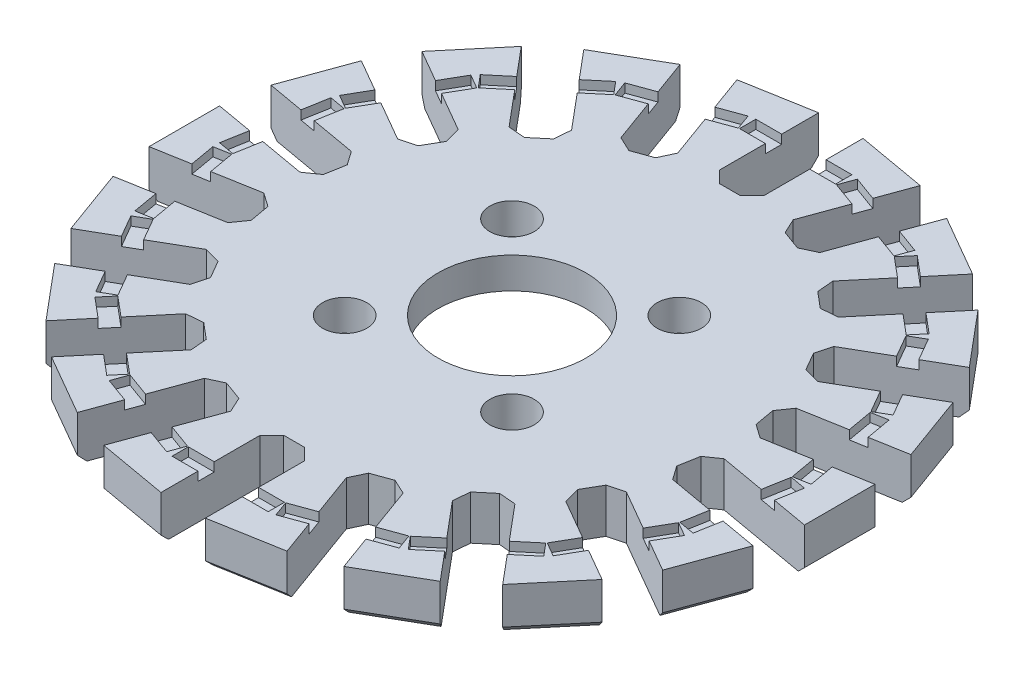
SolidWorks part; units mm, degrees
ref_plane "Front Plane" through (0, 0, 0) normal (0, 0, 1) x (1, 0, 0)
ref_plane "Top Plane" through (0, 0, 0) normal (0, 1, 0) x (1, 0, 0)
ref_plane "Right Plane" through (0, 0, 0) normal (1, 0, 0) x (0, 0, -1)
sketch "Sketch1" plane through (0, 0, 0) normal (0, 1, 0) x (1, 0, 0)
  line L0 (-1.5, 22.2355) -> (-1.5, 14.7355)
  line L1 (-1.5, 22.2355) -> (-6.1955, 21.4076)
  line L2 (-9.0145, 20.3815) -> (-13.1436, 17.9976)
  line L3 (-15.4418, 16.0692) -> (-18.5065, 12.4168)
  line L4 (-20.0065, 9.8187) -> (-21.6372, 5.3384)
  line L5 (-22.1582, 2.3839) -> (-22.1582, -2.3839)
  line L6 (-21.6372, -5.3384) -> (-20.0065, -9.8187)
  line L7 (-18.5065, -12.4168) -> (-15.4418, -16.0692)
  line L8 (-13.1436, -17.9976) -> (-9.0145, -20.3815)
  line L9 (-6.1955, -21.4076) -> (-1.5, -22.2355)
  line L10 (1.5, -22.2355) -> (6.1955, -21.4076)
  line L11 (9.0145, -20.3815) -> (13.1436, -17.9976)
  line L12 (15.4418, -16.0692) -> (18.5065, -12.4168)
  line L13 (20.0065, -9.8187) -> (21.6372, -5.3384)
  line L14 (22.1582, -2.3839) -> (22.1582, 2.3839)
  line L15 (21.6372, 5.3384) -> (20.0065, 9.8187)
  line L16 (18.5065, 12.4168) -> (15.4418, 16.0692)
  line L17 (13.1436, 17.9976) -> (9.0145, 20.3815)
  line L18 (6.1955, 21.4076) -> (1.5, 22.2355)
  line L19 (-1.5, 14.7355) -> (1.5, 14.7355)
  line L20 (1.5, 14.7355) -> (1.5, 22.2355)
  line L21 (6.4494, 13.3338) -> (9.0145, 20.3815)
  line L22 (3.6303, 14.3599) -> (6.4494, 13.3338)
  line L23 (6.1955, 21.4076) -> (3.6303, 14.3599)
  line L24 (10.6209, 10.3239) -> (15.4418, 16.0692)
  line L25 (8.3227, 12.2522) -> (10.6209, 10.3239)
  line L26 (13.1436, 17.9976) -> (8.3227, 12.2522)
  line L27 (13.5113, 6.0687) -> (20.0065, 9.8187)
  line L28 (12.0113, 8.6668) -> (13.5113, 6.0687)
  line L29 (18.5065, 12.4168) -> (12.0113, 8.6668)
  line L30 (14.7721, 1.0816) -> (22.1582, 2.3839)
  line L31 (14.2512, 4.036) -> (14.7721, 1.0816)
  line L32 (21.6372, 5.3384) -> (14.2512, 4.036)
  line L33 (14.2512, -4.036) -> (21.6372, -5.3384)
  line L34 (14.7721, -1.0816) -> (14.2512, -4.036)
  line L35 (22.1582, -2.3839) -> (14.7721, -1.0816)
  line L36 (12.0113, -8.6668) -> (18.5065, -12.4168)
  line L37 (13.5113, -6.0687) -> (12.0113, -8.6668)
  line L38 (20.0065, -9.8187) -> (13.5113, -6.0687)
  line L39 (8.3227, -12.2522) -> (13.1436, -17.9976)
  line L40 (10.6209, -10.3239) -> (8.3227, -12.2522)
  line L41 (15.4418, -16.0692) -> (10.6209, -10.3239)
  line L42 (3.6303, -14.3599) -> (6.1955, -21.4076)
  line L43 (6.4494, -13.3338) -> (3.6303, -14.3599)
  line L44 (9.0145, -20.3815) -> (6.4494, -13.3338)
  line L45 (-1.5, -14.7355) -> (-1.5, -22.2355)
  line L46 (1.5, -14.7355) -> (-1.5, -14.7355)
  line L47 (1.5, -22.2355) -> (1.5, -14.7355)
  line L48 (-6.4494, -13.3338) -> (-9.0145, -20.3815)
  line L49 (-3.6303, -14.3599) -> (-6.4494, -13.3338)
  line L50 (-6.1955, -21.4076) -> (-3.6303, -14.3599)
  line L51 (-10.6209, -10.3239) -> (-15.4418, -16.0692)
  line L52 (-8.3227, -12.2522) -> (-10.6209, -10.3239)
  line L53 (-13.1436, -17.9976) -> (-8.3227, -12.2522)
  line L54 (-13.5113, -6.0687) -> (-20.0065, -9.8187)
  line L55 (-12.0113, -8.6668) -> (-13.5113, -6.0687)
  line L56 (-18.5065, -12.4168) -> (-12.0113, -8.6668)
  line L57 (-14.7721, -1.0816) -> (-22.1582, -2.3839)
  line L58 (-14.2512, -4.036) -> (-14.7721, -1.0816)
  line L59 (-21.6372, -5.3384) -> (-14.2512, -4.036)
  line L60 (-14.2512, 4.036) -> (-21.6372, 5.3384)
  line L61 (-14.7721, 1.0816) -> (-14.2512, 4.036)
  line L62 (-22.1582, 2.3839) -> (-14.7721, 1.0816)
  line L63 (-12.0113, 8.6668) -> (-18.5065, 12.4168)
  line L64 (-13.5113, 6.0687) -> (-12.0113, 8.6668)
  line L65 (-20.0065, 9.8187) -> (-13.5113, 6.0687)
  line L66 (-8.3227, 12.2522) -> (-13.1436, 17.9976)
  line L67 (-10.6209, 10.3239) -> (-8.3227, 12.2522)
  line L68 (-15.4418, 16.0692) -> (-10.6209, 10.3239)
  line L69 (-3.6303, 14.3599) -> (-6.1955, 21.4076)
  line L70 (-6.4494, 13.3338) -> (-3.6303, 14.3599)
  line L71 (-9.0145, 20.3815) -> (-6.4494, 13.3338)
  arc A0 (6.1516, 21.2871) -> (1.5, 22.1073) centre (0, 0) ccw construction
  arc A1 (13.0613, 17.8994) -> (8.9707, 20.2611) centre (0, 0) ccw construction
  arc A2 (18.3955, 12.3527) -> (15.3594, 15.971) centre (0, 0) ccw construction
  arc A3 (21.511, 5.3161) -> (19.8955, 9.7546) centre (0, 0) ccw construction
  arc A4 (22.032, -2.3617) -> (22.032, 2.3617) centre (0, 0) ccw construction
  arc A5 (19.8955, -9.7546) -> (21.511, -5.3161) centre (0, 0) ccw construction
  arc A6 (-8.9707, 20.2611) -> (-13.0613, 17.8994) centre (0, 0) ccw construction
  arc A7 (-15.3594, 15.971) -> (-18.3955, 12.3527) centre (0, 0) ccw construction
  arc A8 (-19.8955, 9.7546) -> (-21.511, 5.3161) centre (0, 0) ccw construction
  arc A9 (-22.032, 2.3617) -> (-22.032, -2.3617) centre (0, 0) ccw construction
  arc A10 (-21.511, -5.3161) -> (-19.8955, -9.7546) centre (0, 0) ccw construction
  arc A11 (-18.3955, -12.3527) -> (-15.3594, -15.971) centre (0, 0) ccw construction
  arc A12 (-13.0613, -17.8994) -> (-8.9707, -20.2611) centre (0, 0) ccw construction
  arc A13 (-6.1516, -21.2871) -> (-1.5, -22.1073) centre (0, 0) ccw construction
  arc A14 (1.5, -22.1073) -> (6.1516, -21.2871) centre (0, 0) ccw construction
  arc A15 (8.9707, -20.2611) -> (13.0613, -17.8994) centre (0, 0) ccw construction
  arc A16 (15.3594, -15.971) -> (18.3955, -12.3527) centre (0, 0) ccw construction
  arc A17 (-1.5, 22.1073) -> (-6.1516, 21.2871) centre (0, 0) ccw construction
  point P96 (0, 0)
  dimension "D1" = 44.3163
  dimension "D2" = 3
  dimension "D3" = 1.5
  dimension "D4" = 7.5
  dimension "D5" = 18
extrude "Boss-Extrude1" add sketch "Sketch1" along normal blind 3
chamfer "Chamfer1" distance 0.8 angle 45 36 edges at (-10.6209, 1.5, 10.3239) (-8.3227, 1.5, 12.2522) (-3.6303, 1.5, 14.3599) (1.5, 1.5, 14.7355) (6.4494, 1.5, 13.3338) (10.6209, 1.5, 10.3239) (13.5113, 1.5, 6.0687) (-6.4494, 1.5, 13.3338) (-1.5, 1.5, 14.7355) (3.6303, 1.5, 14.3599) (8.3227, 1.5, 12.2522) (12.0113, 1.5, 8.6668) (14.7721, 1.5, 1.0816) (14.2512, 1.5, -4.036) (12.0113, 1.5, -8.6668) (8.3227, 1.5, -12.2522) (14.2512, 1.5, 4.036) (14.7721, 1.5, -1.0816) (13.5113, 1.5, -6.0687) (10.6209, 1.5, -10.3239) (3.6303, 1.5, -14.3599) (-1.5, 1.5, -14.7355) (-13.5113, 1.5, -6.0687) (-10.6209, 1.5, -10.3239) (-6.4494, 1.5, -13.3338) (1.5, 1.5, -14.7355) (-3.6303, 1.5, -14.3599) (-8.3227, 1.5, -12.2522) (-12.0113, 1.5, -8.6668) (-14.7721, 1.5, -1.0816) (-14.2512, 1.5, -4.036) (-14.2512, 1.5, 4.036) (-14.7721, 1.5, 1.0816) (-12.0113, 1.5, 8.6668) (-13.5113, 1.5, 6.0687) (6.4494, 1.5, -13.3338)
sketch "Sketch2" plane through (0, 3, 0) normal (0, 1, 0) x (1, 0, 0)
  line L0 (-3.25, 19.7355) -> (3.25, 19.7355)
  line L2 (3.25, 19.7355) -> (3.25, 18.6355)
  line L3 (3.25, 18.6355) -> (-3.25, 18.6355)
  line L4 (-3.25, 18.6355) -> (-3.25, 19.7355)
  line L73 (3.3197, 18.6232) -> (3.6959, 19.6569)
  line L74 (3.6959, 19.6569) -> (9.8039, 17.4337)
  line L75 (9.8039, 17.4337) -> (9.4277, 16.4001)
  line L76 (9.4277, 16.4001) -> (3.3197, 18.6232)
  line L77 (9.489, 16.3647) -> (10.1961, 17.2073)
  line L78 (10.1961, 17.2073) -> (15.1754, 13.0292)
  line L79 (15.1754, 13.0292) -> (14.4683, 12.1866)
  line L80 (14.4683, 12.1866) -> (9.489, 16.3647)
  line L81 (14.5138, 12.1323) -> (15.4665, 12.6823)
  line L82 (15.4665, 12.6823) -> (18.7165, 7.0532)
  line L83 (18.7165, 7.0532) -> (17.7638, 6.5032)
  line L84 (17.7638, 6.5032) -> (14.5138, 12.1323)
  line L85 (17.788, 6.4366) -> (18.8713, 6.6277)
  line L86 (18.8713, 6.6277) -> (20, 0.2264)
  line L87 (20, 0.2264) -> (18.9168, 0.0354)
  line L88 (18.9168, 0.0354) -> (17.788, 6.4366)
  line L89 (18.9168, -0.0354) -> (20, -0.2264)
  line L90 (20, -0.2264) -> (18.8713, -6.6277)
  line L91 (18.8713, -6.6277) -> (17.788, -6.4366)
  line L92 (17.788, -6.4366) -> (18.9168, -0.0354)
  line L93 (17.7638, -6.5032) -> (18.7165, -7.0532)
  line L94 (18.7165, -7.0532) -> (15.4665, -12.6823)
  line L95 (15.4665, -12.6823) -> (14.5138, -12.1323)
  line L96 (14.5138, -12.1323) -> (17.7638, -6.5032)
  line L97 (14.4683, -12.1866) -> (15.1754, -13.0292)
  line L98 (15.1754, -13.0292) -> (10.1961, -17.2073)
  line L99 (10.1961, -17.2073) -> (9.489, -16.3647)
  line L100 (9.489, -16.3647) -> (14.4683, -12.1866)
  line L101 (9.4277, -16.4001) -> (9.8039, -17.4337)
  line L102 (9.8039, -17.4337) -> (3.6959, -19.6569)
  line L103 (3.6959, -19.6569) -> (3.3197, -18.6232)
  line L104 (3.3197, -18.6232) -> (9.4277, -16.4001)
  line L105 (3.25, -18.6355) -> (3.25, -19.7355)
  line L106 (3.25, -19.7355) -> (-3.25, -19.7355)
  line L107 (-3.25, -19.7355) -> (-3.25, -18.6355)
  line L108 (-3.25, -18.6355) -> (3.25, -18.6355)
  line L109 (-3.3197, -18.6232) -> (-3.6959, -19.6569)
  line L110 (-3.6959, -19.6569) -> (-9.8039, -17.4337)
  line L111 (-9.8039, -17.4337) -> (-9.4277, -16.4001)
  line L112 (-9.4277, -16.4001) -> (-3.3197, -18.6232)
  line L113 (-9.489, -16.3647) -> (-10.1961, -17.2073)
  line L114 (-10.1961, -17.2073) -> (-15.1754, -13.0292)
  line L115 (-15.1754, -13.0292) -> (-14.4683, -12.1866)
  line L116 (-14.4683, -12.1866) -> (-9.489, -16.3647)
  line L117 (-14.5138, -12.1323) -> (-15.4665, -12.6823)
  line L118 (-15.4665, -12.6823) -> (-18.7165, -7.0532)
  line L119 (-18.7165, -7.0532) -> (-17.7638, -6.5032)
  line L120 (-17.7638, -6.5032) -> (-14.5138, -12.1323)
  line L121 (-17.788, -6.4366) -> (-18.8713, -6.6277)
  line L122 (-18.8713, -6.6277) -> (-20, -0.2264)
  line L123 (-20, -0.2264) -> (-18.9168, -0.0354)
  line L124 (-18.9168, -0.0354) -> (-17.788, -6.4366)
  line L125 (-18.9168, 0.0354) -> (-20, 0.2264)
  line L126 (-20, 0.2264) -> (-18.8713, 6.6277)
  line L127 (-18.8713, 6.6277) -> (-17.788, 6.4366)
  line L128 (-17.788, 6.4366) -> (-18.9168, 0.0354)
  line L129 (-17.7638, 6.5032) -> (-18.7165, 7.0532)
  line L130 (-18.7165, 7.0532) -> (-15.4665, 12.6823)
  line L131 (-15.4665, 12.6823) -> (-14.5138, 12.1323)
  line L132 (-14.5138, 12.1323) -> (-17.7638, 6.5032)
  line L133 (-14.4683, 12.1866) -> (-15.1754, 13.0292)
  line L134 (-15.1754, 13.0292) -> (-10.1961, 17.2073)
  line L135 (-10.1961, 17.2073) -> (-9.489, 16.3647)
  line L136 (-9.489, 16.3647) -> (-14.4683, 12.1866)
  line L137 (-9.4277, 16.4001) -> (-9.8039, 17.4337)
  line L138 (-9.8039, 17.4337) -> (-3.6959, 19.6569)
  line L139 (-3.6959, 19.6569) -> (-3.3197, 18.6232)
  line L140 (-3.3197, 18.6232) -> (-9.4277, 16.4001)
  line L141 (-22.1582, 2.3839) -> (-22.1582, -2.3839) construction
  point P76 (0, 0)
  dimension "D1" = 6.5
  dimension "D2" = 2.5
  dimension "D3" = 3.25
  dimension "D4" = 1.1
  dimension "D6" = 2.1581
  dimension "D7" = 18.6355
  dimension "D5" = 18
extrude "Cut-Extrude1" cut sketch "Sketch2" against normal blind 0.6
chamfer "Chamfer2" distance 0.5 angle 45 18 edges at (-11.0791, 0, 19.1895) (-16.9741, 0, 14.243) (-20.8219, 0, 7.5785) (-22.1582, 0, 0) (-20.8219, 0, -7.5785) (-16.9741, 0, -14.243) (-11.0791, 0, -19.1895) (-3.8477, 0, -21.8215) (3.8477, 0, -21.8215) (11.0791, 0, -19.1895) (16.9741, 0, -14.243) (20.8219, 0, -7.5785) (22.1582, 0, 0) (20.8219, 0, 7.5785) (16.9741, 0, 14.243) (11.0791, 0, 19.1895) (-3.8477, 0, 21.8215) (3.8477, 0, 21.8215)
sketch "Sketch4" plane through (0, 0, 0) normal (0, -1, 0) x (1, 0, 0)
  line L1 (-5.6569, -5.6569) -> (5.6569, -5.6569) construction
  line L2 (-5.6569, -5.6569) -> (-5.6569, 5.6569) construction
  line L3 (-5.6569, 5.6569) -> (5.6569, 5.6569) construction
  line L4 (5.6569, -5.6569) -> (5.6569, 5.6569) construction
  line L5 (-5.6569, -5.6569) -> (5.6569, 5.6569) construction
  line L6 (-5.6569, 5.6569) -> (5.6569, -5.6569) construction
  circle A8 centre (-5.6569, 5.6569) radius 1.5
  circle A9 centre (5.6569, 5.6569) radius 1.5
  circle A10 centre (5.6569, -5.6569) radius 1.5
  circle A11 centre (-5.6569, -5.6569) radius 1.5
  point P0 (0, 0)
  dimension "D1" = 16
  dimension "D2" = 3
extrude "Cut-Extrude4" cut sketch "Sketch4" against normal up to surface (3 mm away) up to face at (0, 3, 0)
sketch "Sketch5" plane through (0, 0, 0) normal (0, -1, 0) x (1, 0, 0)
  circle A0 centre (0, 0) radius 5
  dimension "D1" = 10
extrude "Cut-Extrude5" cut sketch "Sketch5" against normal up to surface (3 mm away) up to face at (-5.6569, 3, -7.1569)
sketch "Sketch6" plane through (0, 0, 0) normal (0, -1, 0) x (1, 0, 0)
  circle A0 centre (0, 0) radius 11
  dimension "D1" = 22
extrude "Cut-Extrude6" cut sketch "Sketch6" against normal blind 0.9
